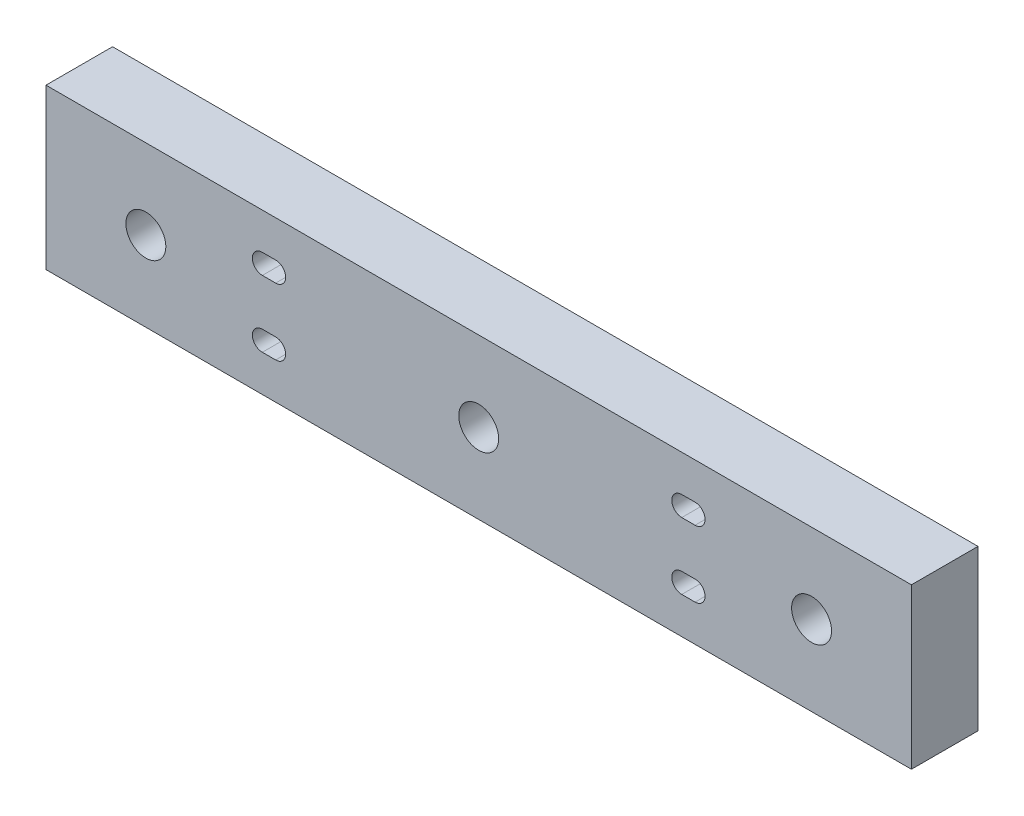
SolidWorks part; units mm, degrees
ref_plane "前视基准面" through (0, 0, 0) normal (0, 0, 1) x (1, 0, 0)
ref_plane "上视基准面" through (0, 0, 0) normal (0, 1, 0) x (1, 0, 0)
ref_plane "右视基准面" through (0, 0, 0) normal (1, 0, 0) x (0, 0, -1)
sketch "草图1" plane through (0, 0, 0) normal (0, 0, 1) x (1, 0, 0)
  line L0 (0, 47.3613) -> (0, -79.6327) construction
  line L1 (-25.5482, 0) -> (49.7517, 0) construction
  line L2 (32.5, 6.5) -> (30.5, 6.5)
  line L7 (-31.5, 5) -> (31.5, -5) construction
  line L8 (-31.5, -5) -> (31.5, 5) construction
  line L9 (32.5, 3.5) -> (30.5, 3.5)
  line L10 (-65, -12) -> (65, -12)
  line L11 (-65, -12) -> (-65, 12)
  line L12 (-65, 12) -> (65, 12)
  line L13 (65, -12) -> (65, 12)
  line L14 (-65, -12) -> (65, 12) construction
  line L15 (-65, 12) -> (65, -12) construction
  line L16 (31.5, 6.8035) -> (31.5, 3.1592) construction
  line L17 (32.5, -6.5) -> (30.5, -6.5)
  line L18 (32.5, -3.5) -> (30.5, -3.5)
  line L19 (-32.5, 6.5) -> (-30.5, 6.5)
  line L20 (-32.5, 3.5) -> (-30.5, 3.5)
  line L21 (-32.5, -6.5) -> (-30.5, -6.5)
  line L22 (-32.5, -3.5) -> (-30.5, -3.5)
  circle A4 centre (-50, 0) radius 3
  circle A5 centre (50, 0) radius 3
  arc A6 (30.5, 6.5) -> (30.5, 3.5) centre (30.5, 5) ccw
  arc A7 (32.5, 6.5) -> (32.5, 3.5) centre (32.5, 5) cw
  arc A8 (32.5, -6.5) -> (32.5, -3.5) centre (32.5, -5) ccw
  arc A9 (30.5, -6.5) -> (30.5, -3.5) centre (30.5, -5) cw
  arc A10 (-32.5, 6.5) -> (-32.5, 3.5) centre (-32.5, 5) ccw
  arc A11 (-30.5, 6.5) -> (-30.5, 3.5) centre (-30.5, 5) cw
  arc A12 (-30.5, -6.5) -> (-30.5, -3.5) centre (-30.5, -5) ccw
  arc A13 (-32.5, -6.5) -> (-32.5, -3.5) centre (-32.5, -5) cw
  circle A14 centre (0, 0) radius 3
  point P3 (0, 0)
  point P14 (0, 0)
  point P28 (31.5, 3.5)
  point P32 (31.5, 6.5)
  point P49 (0, 0)
  dimension "D1" = 15
  dimension "D2" = 15
extrude "凸台-拉伸1" add sketch "草图1" along normal blind 10 contours L12 L13 L10 L11
sketch "草图2" plane through (0, 0, 0) normal (0, 0, -1) x (-1, 0, 0)
  line L0 (-32.5, 6.5) -> (-30.5, 6.5) construction
  line L1 (-32.5, 6.5) -> (-30.5, 6.5)
  line L2 (-34, 5) -> (-28.117, 5) construction
  line L3 (-34, -5) -> (-27.1581, -5) construction
  line L12 (0, 23.1585) -> (0, -21.5945) construction
  arc A0 (-32.5, 6.5) -> (-32.5, 3.5) centre (-32.5, 5) ccw construction
  circle A1 centre (-31.5, 5) radius 4
  arc A2 (-32.5, -3.5) -> (-32.5, -6.5) centre (-32.5, -5) ccw construction
  circle A3 centre (-31.5, -5) radius 4
  circle A4 centre (31.5, -5) radius 4
  circle A5 centre (31.5, 5) radius 4
extrude "切除-拉伸1" cut sketch "草图2" against normal blind 7 contours A1 | A3 | A5 | A4
